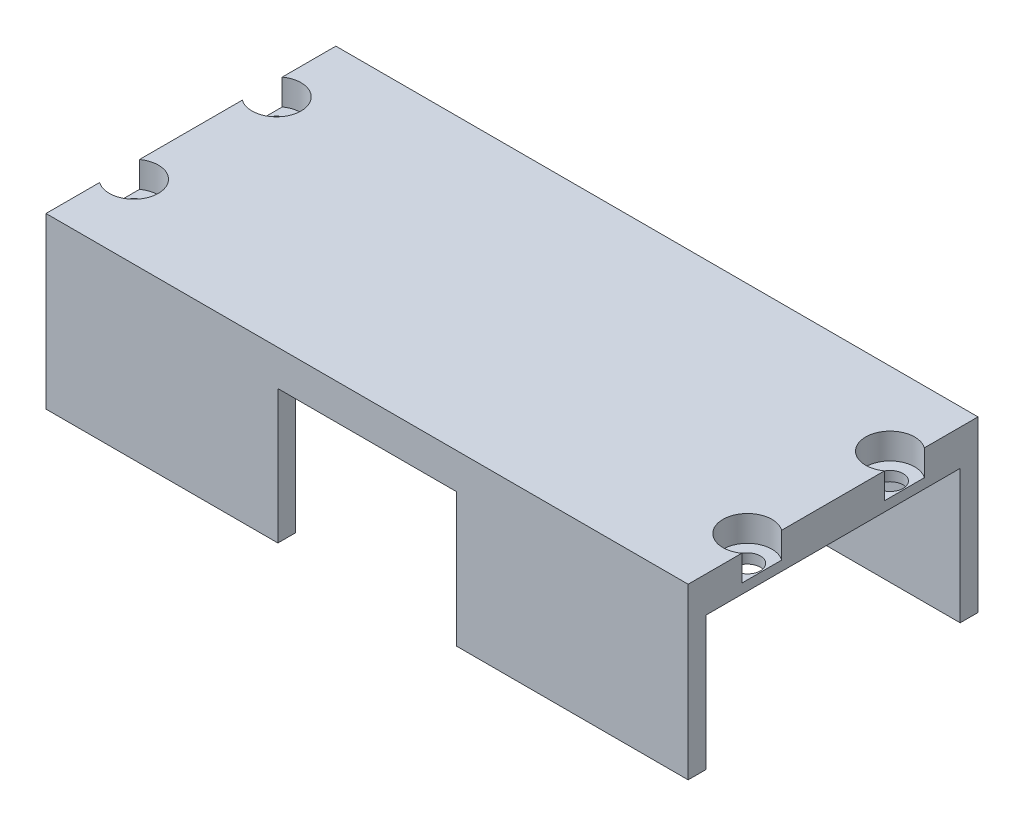
SolidWorks part; units mm, degrees
ref_plane "Front Plane" through (0, 0, 0) normal (0, 0, 1) x (1, 0, 0)
ref_plane "Top Plane" through (0, 0, 0) normal (0, 1, 0) x (1, 0, 0)
ref_plane "Right Plane" through (0, 0, 0) normal (1, 0, 0) x (0, 0, -1)
sketch "Sketch1" plane through (0, 0, 0) normal (0, 1, 0) x (1, 0, 0)
  line L1 (0, 0) -> (72, 0)
  line L2 (0, 0) -> (0, 32.5)
  line L3 (0, 32.5) -> (72, 32.5)
  line L4 (72, 0) -> (72, 32.5)
  dimension "D1" = 32.5
  dimension "D2" = 72
extrude "Boss-Extrude1" add sketch "Sketch1" along normal blind 4
sketch "Sketch4" plane through (0, 4, 0) normal (0, 1, 0) x (1, 0, 0)
  line L0 (36, 32.5) -> (36, -12.4802) construction
  line L1 (72, 32.5) -> (0, 32.5) construction
  line L3 (0, 16.25) -> (122.1673, 16.25) construction
  line L4 (0, 32.5) -> (0, 0) construction
  point P0 (-10.4, 24.25)
  point P12 (1.6, 24.25)
  point P13 (1.6, 8.25)
  point P14 (-10.4, 8.25)
  point P25 (82.4, 8.25)
  point P26 (70.4, 8.25)
  point P27 (70.4, 24.25)
  point P28 (82.4, 24.25)
  dimension "D1" = 2
  dimension "D3" = 12
  dimension "D4" = 16
  dimension "D5" = 8
  dimension "D6" = 34.4
  dimension "D2" = 2
hole_wizard "CBORE for M2.5 Hex Socket Head Cap Screw1" positions "Sketch4" profile "Sketch3" counterbore size "M2.5" standard "DIN" end condition through all
sketch "Sketch3" plane through (-10.4, 4, -24.25) normal (1, 0, 0) x (0, 0, 1)
  line L0 (0, 0) -> (0, 4)
  line L1 (0, 4) -> (1.45, 4)
  line L3 (1.45, 4) -> (1.45, 2.9)
  line L4 (1.45, 2.9) -> (2.75, 2.9)
  line L5 (2.75, 2.9) -> (2.75, 0)
  line L7 (2.75, 0) -> (0, 0)
  line L11 (0, -6.35) -> (0, 107.95) construction
  dimension "Thru Hole Dia." = 2.9
  dimension "Thru Hole Depth" = 4
  dimension "C'Bore Dia." = 5.5
  dimension "C'Bore Depth" = 2.9
sketch "Sketch5" plane through (0, 0, 0) normal (0, -1, 0) x (1, 0, 0)
  line L0 (0, -16.25) -> (72, -16.25) construction
  line L1 (0, 0) -> (72, 0)
  line L2 (0, 0) -> (0, -32.5)
  line L3 (0, -32.5) -> (72, -32.5)
  line L4 (72, 0) -> (72, -32.5)
  line L5 (0, -2) -> (72, -2)
  line L6 (0, -2) -> (0, -30.5)
  line L7 (0, -30.5) -> (72, -30.5)
  line L8 (72, -2) -> (72, -30.5)
  line L9 (0, -16.25) -> (72, -16.25) construction
  line L10 (36, 0) -> (36, -32.5) construction
  line L11 (36, 0) -> (36, -32.5) construction
  line L16 (26, -32.5) -> (46, -32.5)
  line L17 (26, -32.5) -> (26, 0)
  line L18 (26, 0) -> (46, 0)
  line L19 (46, -32.5) -> (46, 0)
  line M25 (0, 0) -> (0, -32.5)
  line M26 (0, -32.5) -> (72, -32.5)
  line M27 (72, -32.5) -> (72, 0)
  line M28 (72, 0) -> (0, 0)
  dimension "D1" = 28.5
  dimension "D2" = 20
extrude "Boss-Extrude2" add sketch "Sketch5" along normal blind 15 contours L5 L17 L1 M25 | L17 L7 M26 M25 | L19 L5 L4 M28 | L19 L7 M26 M27
